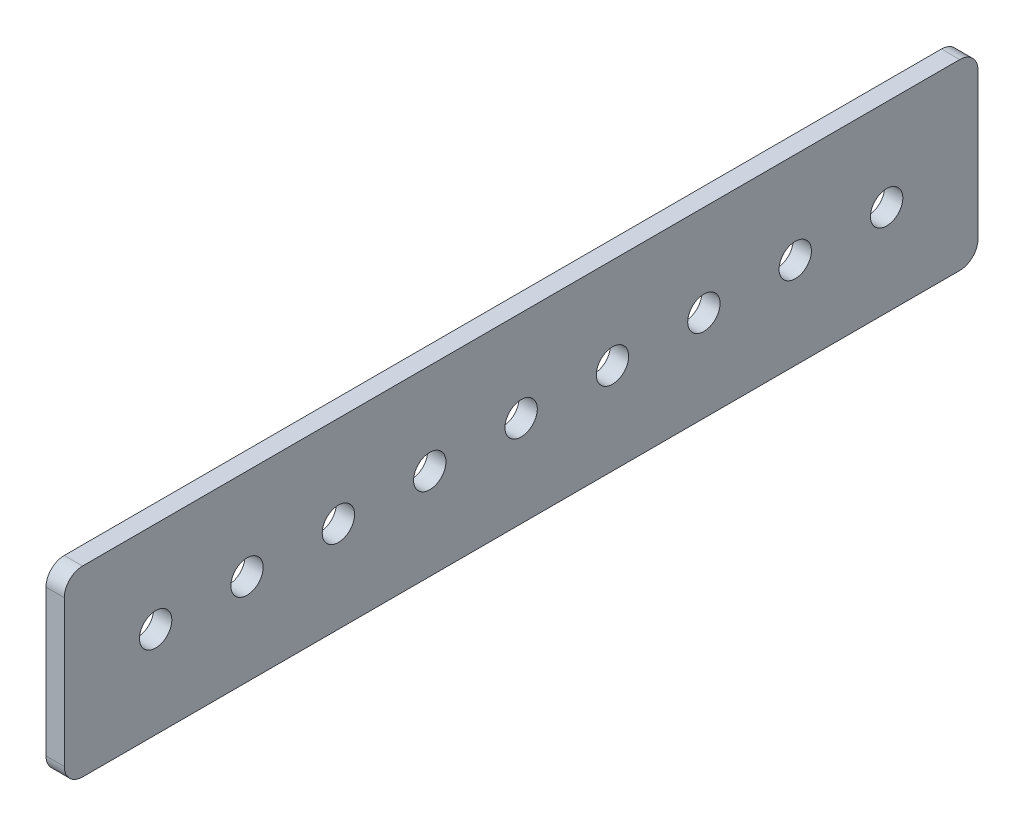
SolidWorks part; units mm, degrees
ref_plane "Front" through (0, 0, 0) normal (0, 0, 1) x (1, 0, 0)
ref_plane "Top" through (0, 0, 0) normal (0, 1, 0) x (1, 0, 0)
ref_plane "Right" through (0, 0, 0) normal (1, 0, 0) x (0, 0, -1)
sketch "Sketch1" plane through (0, 0, 0) normal (1, 0, 0) x (0, 0, -1)
  line L0 (381, -23.749) -> (-381, -23.749) construction
  line L1 (-63.5, -23.749) -> (63.5, -23.749)
  line L2 (-63.5, -23.749) -> (-63.5, 1.651)
  line L4 (63.5, -23.749) -> (63.5, 1.651)
  line L6 (381, 1.651) -> (370.3687, 1.651) construction
  line L8 (63.5, 1.651) -> (-63.5, 1.651)
  circle A1 centre (-50.8, -11.049) radius 2.0701 construction
  circle A2 centre (50.8, -11.049) radius 2.0701 construction
  point P0 (0, 0)
  point P3 (0, 0)
  point P5 (0, 0)
  point P14 (0, 0)
  point P15 (0, 0)
  point P18 (0, 0)
  point P20 (0, 0)
  dimension "D1" = 12.7
  dimension "D2" = 12.7
extrude "Boss-Extrude1" add sketch "Sketch1" along normal blind 2.54 contours L4 L8 L2 L1
hole_wizard "#8 Clearance Hole1" positions "Sketch2" profile "Sketch3" hole size "#8" standard "ANSI Inch" end condition through all
sketch "Sketch2" plane through (0, 0, 0) normal (-1, 0, 0) x (0, 0, 1)
  arc A0 (-48.7313, -10.9728) -> (-52.8687, -10.9728) centre (-50.8, -11.049) ccw construction
  arc A1 (-23.3313, -10.9728) -> (-27.4687, -10.9728) centre (-25.4, -11.049) ccw construction
  arc A2 (2.0687, -10.9728) -> (-2.0687, -10.9728) centre (0, -11.049) ccw construction
  arc A3 (27.4687, -10.9728) -> (23.3313, -10.9728) centre (25.4, -11.049) ccw construction
  arc A4 (52.8687, -10.9728) -> (48.7313, -10.9728) centre (50.8, -11.049) ccw construction
  point P0 (-50.8, -11.049)
  point P2 (-25.4, -11.049)
  point P4 (-38.1, -11.049)
  point P6 (0, -11.049)
  point P8 (25.4, -11.049)
  point P14 (50.8, -11.049)
  point P48 (-12.7, -11.049)
  point P49 (12.7, -11.049)
  point P50 (38.1, -11.049)
  dimension "D1" = 12.7
sketch "Sketch3" plane through (0, -11.049, -50.8) normal (0, 1, 0) x (0, 0, 1)
  line L0 (0, 0) -> (0, 2.54)
  line L1 (0, 2.54) -> (2.2479, 2.54)
  line L2 (2.2479, 2.54) -> (2.2479, 0)
  line L5 (2.2479, 0) -> (0, 0)
  line L11 (0, -6.35) -> (0, 107.95) construction
  dimension "Thru Hole Dia." = 4.4958
  dimension "Thru Hole Depth" = 2.54
fillet "Fillet1" radius 2.54 4 edges at (1.27, -23.749, 63.5) (1.27, -23.749, -63.5) (1.27, 1.651, -63.5) (1.27, 1.651, 63.5)
